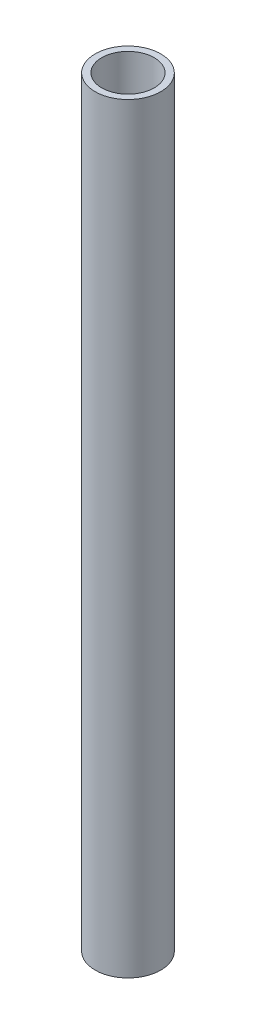
SolidWorks part; units mm, degrees
ref_plane "Front Plane" through (0, 0, 0) normal (0, 0, 1) x (1, 0, 0)
ref_plane "Top Plane" through (0, 0, 0) normal (0, 1, 0) x (1, 0, 0)
ref_plane "Right Plane" through (0, 0, 0) normal (1, 0, 0) x (0, 0, -1)
sketch "Sketch2" plane through (0, 0, 0) normal (0, 1, 0) x (1, 0, 0)
  circle A0 centre (0, 0) radius 15.875
  circle A2 centre (0, 0) radius 12.7
  dimension "D1" = 31.75
  dimension "D2" = 25.4
extrude "Boss-Extrude1" add sketch "Sketch2" along normal blind 368.3
sketch "Sketch3" [suppressed] plane through (0, 0, 0) normal (0, 0, 1) x (1, 0, 0)
  circle A0 centre (0, 50.8) radius 3.175
  dimension "D1" = 6.35
  dimension "D2" = 50.8
sketch "Sketch4" [suppressed] plane through (0, 0, 0) normal (0, 0, 1) x (1, 0, 0)
  circle A0 centre (0, 50.8) radius 3.175
  dimension "D1" = 6.35
  dimension "D2" = 50.8
extrude "Cut-Extrude2" [suppressed] cut sketch "Sketch4" against normal through all both and the other way through all
extrude "Cut-Extrude3" [suppressed] cut sketch "Sketch3" against normal through all both and the other way through all
